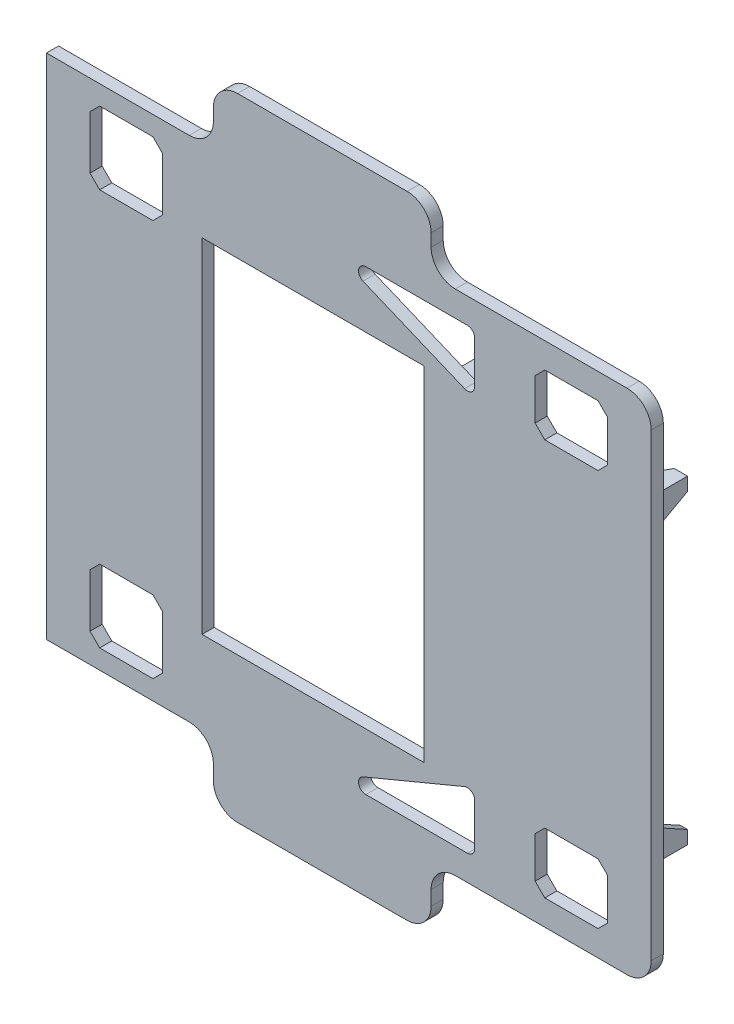
SolidWorks part; units mm, degrees
ref_plane "前视基准面" through (0, 0, 0) normal (0, 0, 1) x (1, 0, 0)
ref_plane "上视基准面" through (0, 0, 0) normal (0, 1, 0) x (1, 0, 0)
ref_plane "右视基准面" through (0, 0, 0) normal (1, 0, 0) x (0, 0, -1)
sketch "草图1" plane through (0, 0, 0) normal (0, 0, 1) x (1, 0, 0)
  line L0 (-45, 115) -> (-45, 120)
  line L1 (-114, 105) -> (-55, 105)
  line L2 (-114, 95) -> (-114, -95)
  line L3 (-114, -105) -> (-55, -105)
  line L4 (136, 95) -> (136, -95)
  line L5 (-114, 95) -> (-114, 105)
  line L7 (-35, 130) -> (35.1247, 130)
  line L8 (45, 120.1247) -> (45, 115)
  line L9 (-45, -115) -> (-45, -121.0101)
  line L10 (-35, -131.0101) -> (35, -131.0101)
  line L11 (45, -121.0101) -> (45, -115)
  line L12 (55, 105) -> (126, 105)
  line L13 (55, -105) -> (115, -105)
  line L15 (132.8114, 102.3216) -> (136, 105) construction
  line L16 (-159.0816, 0) -> (162.8742, 0) construction
  line L17 (0, -160.1649) -> (0, 164.862) construction
  line L18 (-114, -95) -> (-114, -105)
  line L22 (126, -105) -> (115, -105)
  arc A2 (136, 95) -> (126, 105) centre (126, 95) ccw
  arc A4 (-55, 105) -> (-45, 115) centre (-55, 115) ccw
  arc A5 (55, 105) -> (45, 115) centre (55, 115) cw
  arc A6 (-35, 130) -> (-45, 120) centre (-35, 120) ccw
  arc A7 (45, 120.1247) -> (35.1247, 130) centre (35.1247, 120.1247) ccw
  arc A8 (-45, -115) -> (-55, -105) centre (-55, -115) ccw
  arc A9 (45, -115) -> (55, -105) centre (55, -115) cw
  arc A10 (-35, -131.0101) -> (-45, -121.0101) centre (-35, -121.0101) cw
  arc A11 (35, -131.0101) -> (45, -121.0101) centre (35, -121.0101) ccw
  arc A13 (126, -105) -> (136, -95) centre (126, -95) ccw
  point P0 (0, 0)
  point P28 (-45.35, 105)
  point P32 (45, 105)
  point P40 (45, -105)
  dimension "D2" = 45
  dimension "D3" = 10
  dimension "D4" = 45
  dimension "D5" = 10
  dimension "D6" = 10
  dimension "D9" = 10
  dimension "D11" = 9.8753
  dimension "D7" = 10
  dimension "D8" = 10
  dimension "D10" = 10
  dimension "D12" = 10
  dimension "D13" = 210
  dimension "D14" = 59
  dimension "D15" = 59
extrude "凸台-拉伸1" add sketch "草图1" along normal blind 5
sketch "草图10" plane through (0, 0, 0) normal (0, 0, -1) x (-1, 0, 0)
  line L1 (-150, 150) -> (150, 150)
  line L2 (-150, 150) -> (-150, -150)
  line L3 (-150, -150) -> (150, -150)
  line L4 (150, 150) -> (150, -150)
  line L5 (-150, 150) -> (150, -150) construction
  line L6 (-150, -150) -> (150, 150) construction
  point P0 (0, 0)
  dimension "D1" = 300
sketch "草图2" plane through (0, 0, 5) normal (0, 0, 1) x (1, 0, 0)
  line L0 (136, -95) -> (136, 95) construction
  line L1 (-96, 97) -> (-66, 97)
  line L2 (-96, 97) -> (-96, 67)
  line L3 (-96, 67) -> (-66, 67)
  line L4 (-66, 97) -> (-66, 67)
  line L5 (-96, 97) -> (-66, 67) construction
  line L6 (-96, 67) -> (-66, 97) construction
  line L7 (-96, -67) -> (-66, -67)
  line L8 (-96, -67) -> (-96, -97)
  line L9 (-96, -97) -> (-66, -97)
  line L10 (-66, -67) -> (-66, -97)
  line L11 (-96, -67) -> (-66, -97) construction
  line L12 (-96, -97) -> (-66, -67) construction
  line L13 (88, 94.5) -> (118, 94.5)
  line L14 (88, 94.5) -> (88, 69.5)
  line L15 (88, 69.5) -> (118, 69.5)
  line L16 (118, 94.5) -> (118, 69.5)
  line L17 (88, 94.5) -> (118, 69.5) construction
  line L18 (88, 69.5) -> (118, 94.5) construction
  line L19 (88, -69.5) -> (118, -69.5)
  line L20 (88, -69.5) -> (88, -94.5)
  line L21 (88, -94.5) -> (118, -94.5)
  line L22 (118, -69.5) -> (118, -94.5)
  line L23 (88, -69.5) -> (118, -94.5) construction
  line L24 (88, -94.5) -> (118, -69.5) construction
  line L25 (3, 94.5) -> (63, 94.5)
  line L28 (63, 94.5) -> (63, 69.5)
  line L29 (3, 94.5) -> (63, 69.5) construction
  line L30 (33, 82) -> (63, 94.5) construction
  line L33 (3, -94.5) -> (63, -94.5)
  line L34 (63, -69.5) -> (63, -94.5)
  line L35 (33, -82) -> (63, -94.5) construction
  line L36 (3, -94.5) -> (63, -69.5) construction
  line L37 (-55, 105) -> (-114, 105) construction
  line L38 (-114, -105) -> (-55, -105) construction
  line L39 (-114, 105) -> (-114, -105) construction
  line L40 (3, 94.5) -> (63, 69.5)
  line L41 (3, -94.5) -> (63, -69.5)
  point P0 (-81, 82)
  point P5 (-81, -82)
  point P10 (103, 82)
  point P15 (103, -82)
  point P20 (33, 82)
  point P25 (33, -82)
  dimension "D1" = 8
  dimension "D2" = 8
  dimension "D3" = 18
  dimension "D4" = 18
  dimension "D5" = 30
  dimension "D6" = 30
  dimension "D7" = 18
  dimension "D8" = 18
  dimension "D9" = 25
  dimension "D10" = 30
  dimension "D12" = 60
  dimension "D13" = 25
  dimension "D14" = 30
  dimension "D15" = 30
  dimension "D16" = 25
  dimension "D17" = 25
  dimension "D18" = 25
  dimension "D19" = 25
extrude "切除-拉伸1" cut sketch "草图2" against normal through all
chamfer "倒角1" distance 4 angle 45 16 edges at (-96, 67, 2.5) (-96, -97, 2.5) (88, -94.5, 2.5) (-96, 97, 2.5) (-96, -67, 2.5) (88, -69.5, 2.5) (-66, -97, 2.5) (-66, 67, 2.5) (118, -94.5, 2.5) (-66, -67, 2.5) (118, -69.5, 2.5) (-66, 97, 2.5) (88, 69.5, 2.5) (88, 94.5, 2.5) (118, 69.5, 2.5) (118, 94.5, 2.5)
sketch "草图3" plane through (0, 0, 0) normal (0, 0, -1) x (-1, 0, 0)
  line L0 (-166.2651, 0) -> (135.0615, 0) construction
  line L1 (-131, 66) -> (-131, 55)
  line L2 (-131, 55) -> (-128, 55)
  line L3 (-128, 55) -> (-128, 63)
  line L4 (-128, 63) -> (-120, 63)
  line L5 (-120, 63) -> (-120, 66)
  line L6 (-120, 66) -> (-131, 66)
  line L7 (-56, 63) -> (-56, 66)
  line L8 (-56, 66) -> (-45, 66)
  line L9 (-45, 66) -> (-45, 55)
  line L10 (-45, 55) -> (-48, 55)
  line L11 (-48, 55) -> (-48, 63)
  line L12 (-48, 63) -> (-56, 63)
  line L13 (-136, -95) -> (-136, 95) construction
  line L14 (-48, -63) -> (-56, -63)
  line L15 (-48, -55) -> (-48, -63)
  line L16 (-45, -55) -> (-48, -55)
  line L17 (-45, -66) -> (-45, -55)
  line L18 (-56, -63) -> (-56, -66)
  line L19 (-120, -63) -> (-120, -66)
  line L20 (-128, -63) -> (-120, -63)
  line L21 (-128, -55) -> (-128, -63)
  line L22 (-131, -55) -> (-128, -55)
  line L23 (-131, -66) -> (-131, -55)
  line L24 (-120, -66) -> (-131, -66)
  line L25 (-56, -66) -> (-45, -66)
  dimension "D1" = 3
  dimension "D2" = 3
  dimension "D3" = 3
  dimension "D4" = 3
  dimension "D5" = 80
  dimension "D6" = 63
  dimension "D7" = 8
  dimension "D8" = 5
extrude "凸台-拉伸2" add sketch "草图3" along normal blind 15
sketch "草图4" plane through (131, 0, 0) normal (1, 0, 0) x (0, 0, -1)
  line L0 (15, 60.5) -> (5, 55)
  line L1 (15, 66) -> (15, 55) construction
  line L2 (15, 55) -> (0, 55) construction
  line L3 (5, 55) -> (15, 55)
  line L4 (15, 55) -> (15, 60.5)
  line L5 (15, -60.5) -> (15, -55)
  line L6 (15, -55) -> (15, -66) construction
  line L7 (15, -55) -> (5, -55)
  line L8 (15, -55) -> (0, -55) construction
  line L9 (5, -55) -> (15, -60.5)
  dimension "D1" = 10
  dimension "D2" = 10
extrude "切除-拉伸2" cut sketch "草图4" against normal blind 3
sketch "草图5" plane through (0, 66, 0) normal (0, 1, 0) x (1, 0, 0)
  line L0 (50.5, 15) -> (56, 15)
  line L1 (45, 15) -> (56, 15) construction
  line L2 (56, 15) -> (56, 5)
  line L3 (56, 15) -> (56, 0) construction
  line L4 (56, 5) -> (50.5, 15)
  line L5 (120, 15) -> (125.5, 15)
  line L6 (120, 15) -> (131, 15) construction
  line L7 (125.5, 15) -> (120, 5)
  line L8 (120, 15) -> (120, 0) construction
  line L9 (120, 5) -> (120, 15)
  dimension "D1" = 10
  dimension "D2" = 10
extrude "切除-拉伸3" cut sketch "草图5" against normal blind 3
sketch "草图6" plane through (45, 0, 0) normal (-1, 0, 0) x (0, 0, 1)
  line L0 (-15, 60.5) -> (-5, 55)
  line L1 (-15, 55) -> (-15, 66) construction
  line L2 (-5, 55) -> (-15, 55)
  line L3 (-15, 55) -> (-15, 60.5)
  line L4 (-15, -60.5) -> (-15, -55)
  line L5 (-15, -55) -> (-5, -55)
  line L6 (-15, -55) -> (0, -55) construction
  line L7 (-5, -55) -> (-15, -60.5)
  dimension "D1" = 10
extrude "切除-拉伸4" cut sketch "草图6" against normal blind 3
sketch "草图7" plane through (0, -66, 0) normal (0, -1, 0) x (1, 0, 0)
  line L0 (50.5, -15) -> (56, -15)
  line L1 (56, -15) -> (45, -15) construction
  line L2 (56, -15) -> (56, -5)
  line L3 (56, -5) -> (50.5, -15)
  line L4 (120, -15) -> (125.5, -15)
  line L5 (131, -15) -> (120, -15) construction
  line L6 (125.5, -15) -> (120, -5)
  line L7 (120, -5) -> (120, -15)
extrude "切除-拉伸5" cut sketch "草图7" against normal blind 3
fillet "圆角1" radius 3 6 edges at (63, 69.5, 2.5) (3, -94.5, 2.5) (3, 94.5, 2.5) (63, -94.5, 2.5) (63, -69.5, 2.5) (63, 94.5, 2.5)
sketch "草图8" plane through (0, 0, 0) normal (0, 0, -1) x (-1, 0, 0)
  line L0 (-42, 71) -> (-42, -71)
  line L1 (-42, -71) -> (49.7, -71)
  line L2 (49.7, -71) -> (49.7, 71)
  line L3 (49.7, 71) -> (-42, 71)
  line L4 (-136, -95) -> (-136, 95) construction
  line L5 (-187.6753, 0) -> (145.1783, 0) construction
  point P9 (49.7, 0)
  dimension "D1" = 94
  dimension "D2" = 142
  dimension "D3" = 91.7
extrude "切除-拉伸6" cut sketch "草图8" against normal blind 5
equation "\"45、\"=43.7672"
